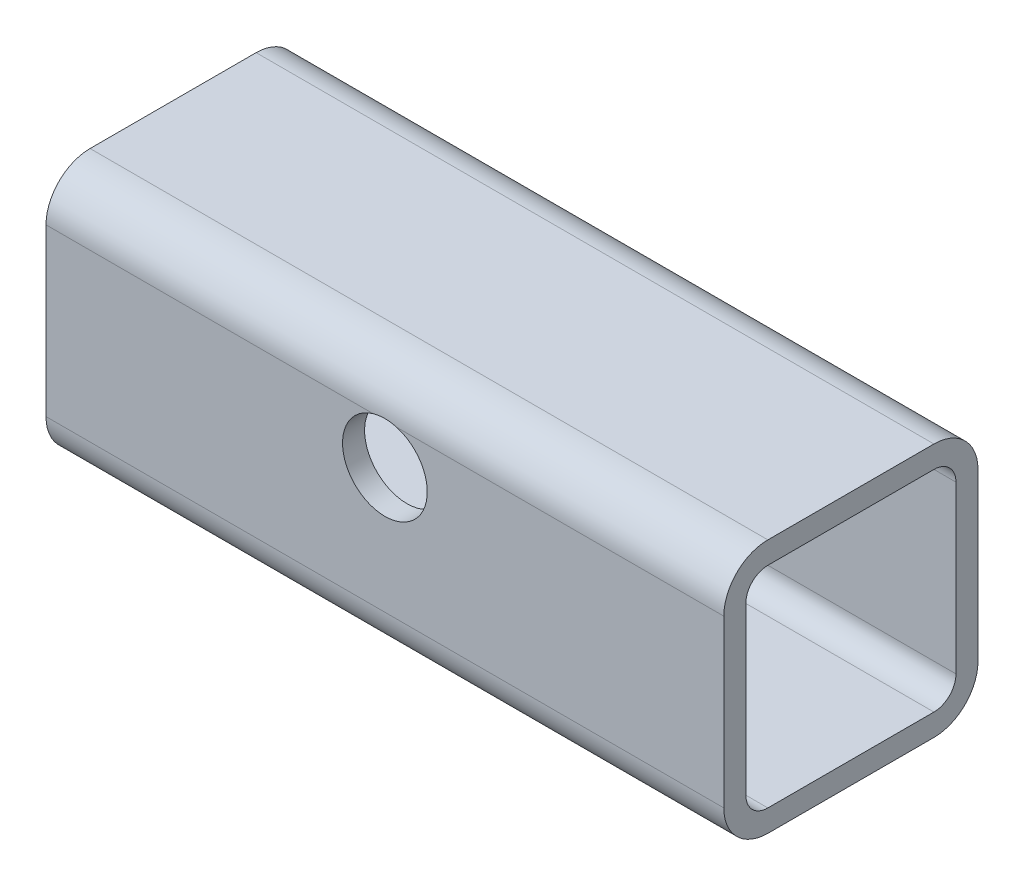
SolidWorks part; units mm, degrees
ref_plane "Płaszczyzna przednia" through (0, 0, 0) normal (0, 0, 1) x (1, 0, 0)
ref_plane "Płaszczyzna górna" through (0, 0, 0) normal (0, 1, 0) x (1, 0, 0)
ref_plane "Płaszczyzna prawa" through (0, 0, 0) normal (1, 0, 0) x (0, 0, -1)
sketch3d "Szkic 3D1"
  line L0 (0, 0, 0) -> (80, 0, 0)
  dimension "D1" = 80
other "Rura kwadratowa 30 X 30 X 2.6(1)"
ref_plane "Płaszczyzna1" through (0, 0, 0) normal (1, 0, 0) x (0, 0, -1)
sketch "Sketch11" plane through (0, 0, 0) normal (1, 0, 0) x (0, 0, -1)
  line L0 (-9.8, -12.4) -> (9.8, -12.4)
  line L1 (-12.4, -9.8) -> (-12.4, 9.8)
  line L2 (9.8, 12.4) -> (-9.8, 12.4)
  line L3 (12.4, 9.8) -> (12.4, -9.8)
  line L4 (-9.8, -15) -> (9.8, -15)
  line L5 (-15, -9.8) -> (-15, 9.8)
  line L6 (9.8, 15) -> (-9.8, 15)
  line L7 (15, 9.8) -> (15, -9.8)
  arc A0 (15, 9.8) -> (9.8, 15) centre (9.8, 9.8) ccw
  arc A1 (9.8, -15) -> (15, -9.8) centre (9.8, -9.8) ccw
  arc A2 (-15, -9.8) -> (-9.8, -15) centre (-9.8, -9.8) ccw
  arc A3 (-9.8, 15) -> (-15, 9.8) centre (-9.8, 9.8) ccw
  arc A4 (-9.8, 12.4) -> (-12.4, 9.8) centre (-9.8, 9.8) ccw
  arc A5 (12.4, 9.8) -> (9.8, 12.4) centre (9.8, 9.8) ccw
  arc A6 (9.8, -12.4) -> (12.4, -9.8) centre (9.8, -9.8) ccw
  arc A7 (-12.4, -9.8) -> (-9.8, -12.4) centre (-9.8, -9.8) ccw
  point P0 (-15, 0)
  point P1 (15, 0)
  point P2 (0, 15)
  point P3 (0, -15)
  point P4 (0, 0)
  point P5 (-15, -15)
  point P6 (15, -15)
  point P7 (15, 15)
  point P8 (-15, 15)
  point P33 (0, 0)
  dimension "D1" = 5.2
  dimension "Thickness" = 2.6
  dimension "V_leg" = 30
sketch "Szkic3" plane through (0, 0, 15) normal (0, 0, 1) x (1, 0, 0)
  line L0 (40, 28.5653) -> (40, -28.7455) construction
  line L1 (80, 9.8) -> (80, -9.8) construction
  line L2 (0, 9.8) -> (0, -9.8) construction
  line L5 (80, 15) -> (0, 15) construction
  circle A0 centre (40, 5) radius 5
  point P8 (0, 0)
  point P9 (0, 0)
  dimension "D1" = 10
  dimension "D2" = 10
extrude "Wytnij-wyciągnięcie1" cut sketch "Szkic3" against normal through all
